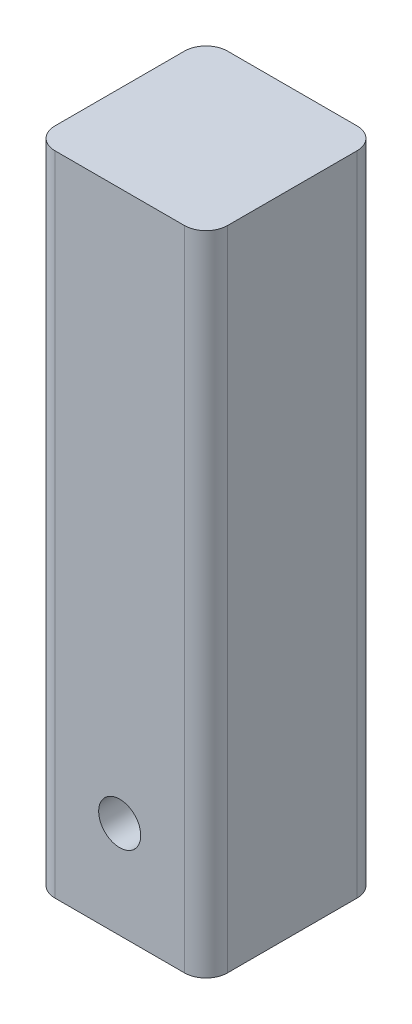
SolidWorks part; units mm, degrees
ref_plane "Alzado" through (0, 0, 0) normal (0, 0, 1) x (1, 0, 0)
ref_plane "Planta" through (0, 0, 0) normal (0, 1, 0) x (1, 0, 0)
ref_plane "Vista lateral" through (0, 0, 0) normal (1, 0, 0) x (0, 0, -1)
sketch "Croquis2" plane through (0, 0, 0) normal (0, 1, 0) x (1, 0, 0)
  line L1 (-44.837, 15.4563) -> (-20.837, 15.4563)
  line L2 (-48.837, 11.4563) -> (-48.837, -12.5437)
  line L3 (-44.837, -16.5437) -> (-20.837, -16.5437)
  line L4 (-16.837, 11.4563) -> (-16.837, -12.5437)
  arc A0 (-44.837, 15.4563) -> (-48.837, 11.4563) centre (-44.837, 11.4563) ccw
  arc A1 (-48.837, -12.5437) -> (-44.837, -16.5437) centre (-44.837, -12.5437) ccw
  arc A2 (-16.837, -12.5437) -> (-20.837, -16.5437) centre (-20.837, -12.5437) cw
  arc A3 (-16.837, 11.4563) -> (-20.837, 15.4563) centre (-20.837, 11.4563) ccw
  point P6 (-48.837, 15.4563)
  point P11 (-16.837, -16.5437)
  point P14 (-16.837, 15.4563)
  dimension "D3" = 4
  dimension "D1" = 32
  dimension "D2" = 32
extrude "Saliente-Extruir1" add sketch "Croquis2" along normal blind 120
sketch "Croquis3" plane through (0, 0, 16.5437) normal (0, 0, 1) x (1, 0, 0)
  circle A0 centre (-32.837, 18) radius 3.9
  dimension "D2" = 7.8
extrude "Cortar-Extruir1" cut sketch "Croquis3" against normal blind 32
